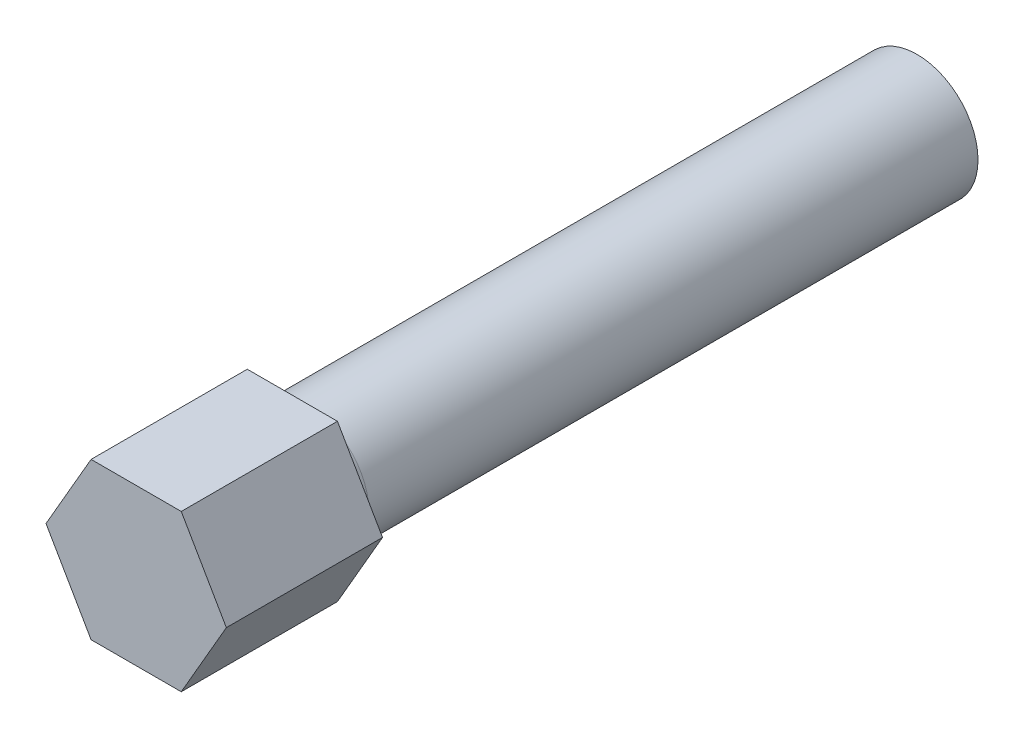
SolidWorks part; units mm, degrees
ref_plane "Front Plane" through (0, 0, 0) normal (0, 0, 1) x (1, 0, 0)
ref_plane "Top Plane" through (0, 0, 0) normal (0, 1, 0) x (1, 0, 0)
ref_plane "Right Plane" through (0, 0, 0) normal (1, 0, 0) x (0, 0, -1)
sketch "Sketch2" plane through (0, 0, 0) normal (0, 0, 1) x (1, 0, 0)
  circle A0 centre (0, 0) radius 4.953
  circle A1 centre (0, 0) radius 2.032
  dimension "D1" = 9.906
  dimension "D2" = 4.064
extrude "Boss-Extrude1" add sketch "Sketch2" along normal blind 50.8
sketch "Sketch3" plane through (0, 0, 0) normal (0, 0, -1) x (-1, 0, 0)
  line L1 (4.6927, 0) -> (2.3464, 4.064)
  line L2 (2.3464, 4.064) -> (-2.3464, 4.064)
  line L3 (-2.3464, 4.064) -> (-4.6927, 0)
  line L4 (-4.6927, 0) -> (-2.3464, -4.064)
  line L5 (-2.3464, -4.064) -> (2.3464, -4.064)
  line L6 (2.3464, -4.064) -> (4.6927, 0)
  circle A0 centre (0, 0) radius 4.064 construction
  dimension "D1" = 8.128
  dimension "D2" = 4.064
extrude "Cut-Extrude1" cut sketch "Sketch3" against normal blind 3.302
sketch "Sketch4" plane through (0, 0, 50.8) normal (0, 0, 1) x (1, 0, 0)
  line L1 (7.3323, 0) -> (3.6662, 6.35)
  line L2 (3.6662, 6.35) -> (-3.6662, 6.35)
  line L3 (-3.6662, 6.35) -> (-7.3323, 0)
  line L4 (-7.3323, 0) -> (-3.6662, -6.35)
  line L5 (-3.6662, -6.35) -> (3.6662, -6.35)
  line L6 (3.6662, -6.35) -> (7.3323, 0)
  circle A0 centre (0, 0) radius 6.35 construction
  dimension "D1" = 12.7
  dimension "D2" = 6.35
extrude "Boss-Extrude2" add sketch "Sketch4" along normal blind 12.7
fillet "Fillet1" radius 1.27 1 edges at (4.953, 0, 50.8)
